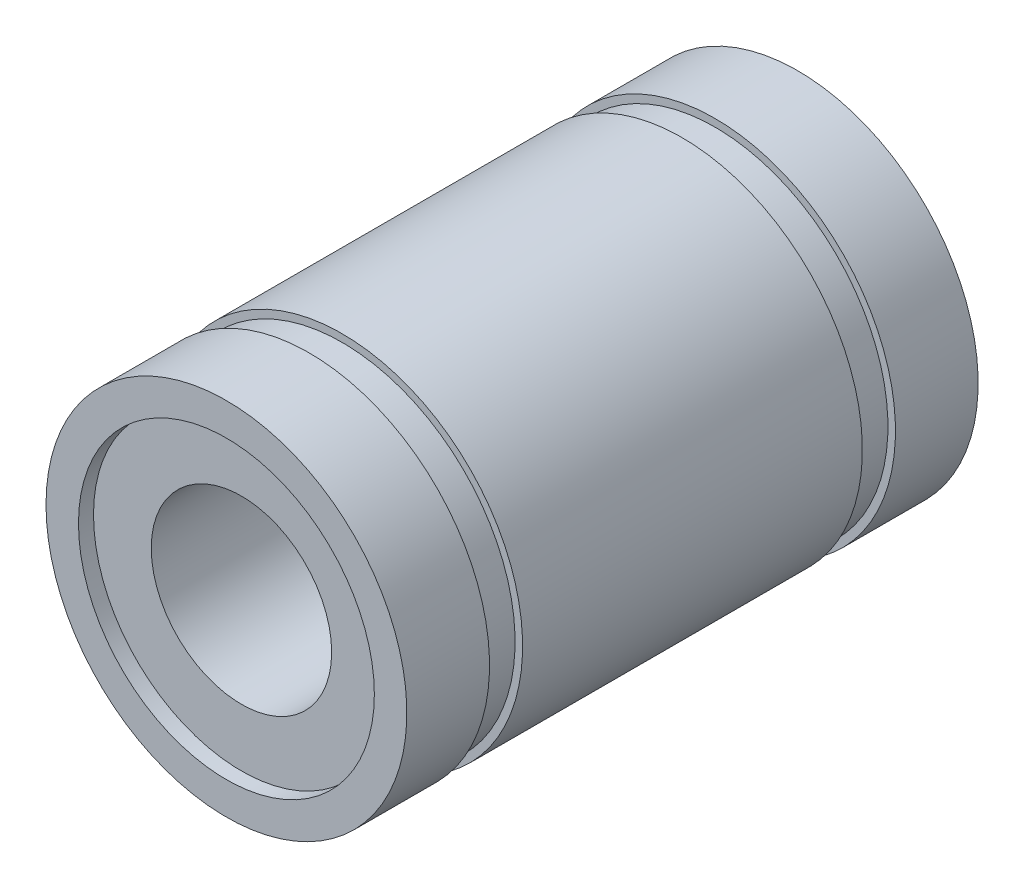
SolidWorks part; units mm, degrees
ref_plane "Front Plane" through (0, 0, 0) normal (0, 0, 1) x (1, 0, 0)
ref_plane "Top Plane" through (0, 0, 0) normal (0, 1, 0) x (1, 0, 0)
ref_plane "Right Plane" through (0, 0, 0) normal (1, 0, 0) x (0, 0, -1)
ref_plane "Plane1" through (0, 0, 0) normal (0, -1, 0) x (1, 0, 0)
sketch "Sketch1" plane through (0, 0, 0) normal (0, -1, 0) x (1, 0, 0)
  line L0 (6, 16.25) -> (6, 19)
  line L1 (6, 19) -> (4.92, 19)
  line L2 (4.92, 19) -> (4.92, 18.5)
  line L3 (4.92, 18.5) -> (3, 18.5)
  line L4 (3, 18.5) -> (3, 0.5)
  line L5 (3, 0.5) -> (4.92, 0.5)
  line L6 (4.92, 0.5) -> (4.92, 0)
  line L7 (4.92, 0) -> (6, 0)
  line L8 (6, 0) -> (6, 2.75)
  line L9 (6, 2.75) -> (5.75, 2.75)
  line L10 (5.75, 2.75) -> (5.75, 3.85)
  line L11 (5.75, 3.85) -> (6, 3.85)
  line L12 (6, 3.85) -> (6, 15.15)
  line L13 (6, 15.15) -> (5.75, 15.15)
  line L14 (5.75, 15.15) -> (5.75, 16.25)
  line L15 (5.75, 16.25) -> (6, 16.25)
  line L16 (0, 19) -> (0, 0) construction
revolve "Revolve1" add sketch "Sketch1" angle 360 about L16
